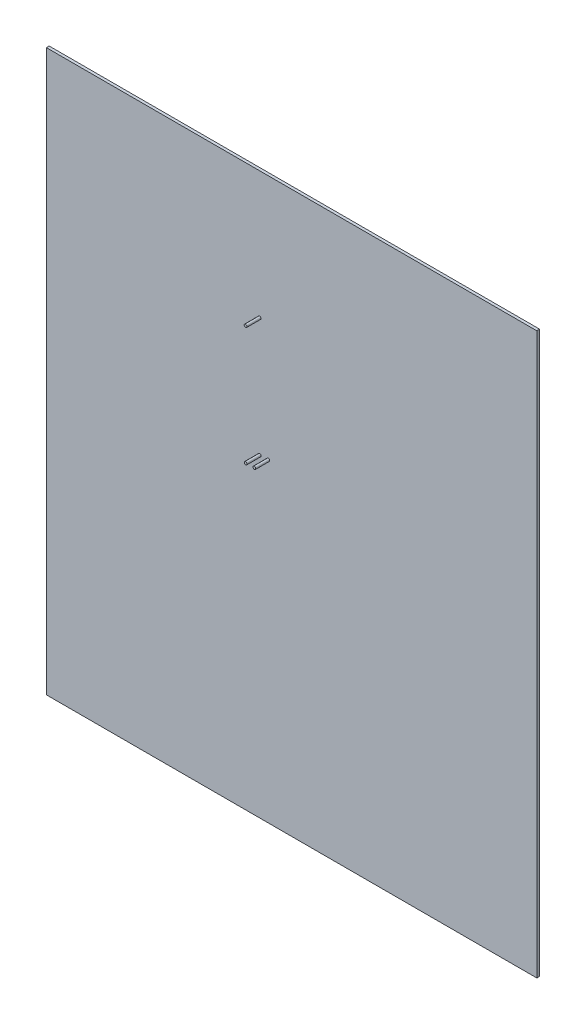
SolidWorks part; units mm, degrees
ref_plane "Plano frontal" through (0, 0, 0) normal (0, 0, 1) x (1, 0, 0)
ref_plane "Plano superior" through (0, 0, 0) normal (0, 1, 0) x (1, 0, 0)
ref_plane "Plano direito" through (0, 0, 0) normal (1, 0, 0) x (0, 0, -1)
sketch "Esboço1" plane through (0, 0, 0) normal (0, 0, 1) x (1, 0, 0)
  line L1 (-175, -200) -> (175, -200)
  line L2 (-175, -200) -> (-175, 200)
  line L3 (-175, 200) -> (175, 200)
  line L4 (175, -200) -> (175, 200)
  line L5 (-175, -200) -> (175, 200) construction
  line L6 (-175, 200) -> (175, -200) construction
  point P0 (0, 0)
  dimension "D1" = 400
  dimension "D2" = 350
extrude "Ressalto-extrusão1" add sketch "Esboço1" along normal blind 2
sketch "Esboço2" plane through (0, 0, 2) normal (0, 0, 1) x (1, 0, 0)
  line L0 (-175, 24.27) -> (-22.77, 24.27) construction
  line L1 (-175, 200) -> (-175, -200) construction
  line L2 (-22.77, 24.27) -> (-22.77, -200) construction
  line L3 (-175, -200) -> (175, -200) construction
  line L4 (-175, 109.16) -> (-22.83, 109.16) construction
  line L6 (-175, 24.5) -> (-16.6, 24.5) construction
  circle A0 centre (-16.6, 24.5) radius 1
  circle A1 centre (-22.77, 24.27) radius 1
  circle A2 centre (-22.83, 109.16) radius 1
  dimension "D1" = 152.17
  dimension "D2" = 224.27
  dimension "D3" = 152.23
  dimension "D4" = 158.4
extrude "Ressalto-extrusão2" add sketch "Esboço2" along normal blind 10
